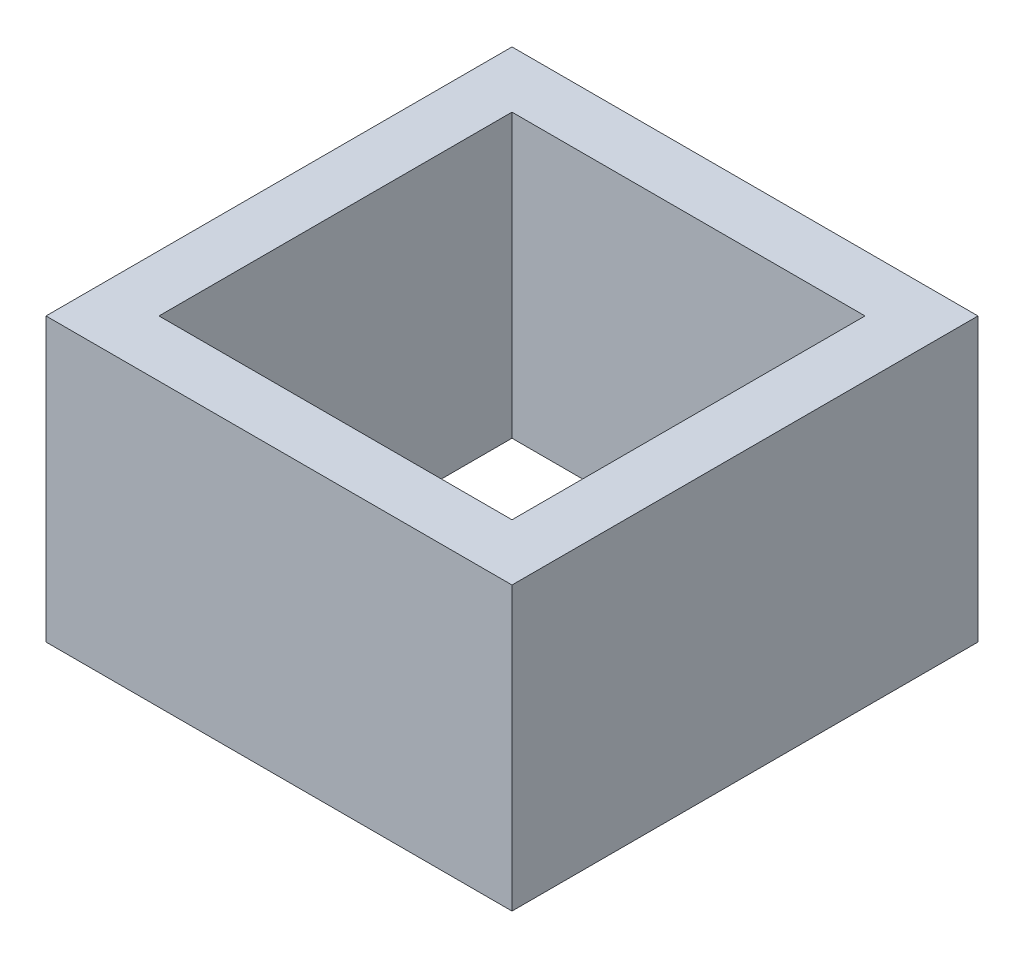
SolidWorks part; units mm, degrees
material "2014-O"
ref_plane "Plan de face" through (0, 0, 0) normal (0, 0, 1) x (1, 0, 0)
ref_plane "Plan de dessus" through (0, 0, 0) normal (0, 1, 0) x (1, 0, 0)
ref_plane "Plan de droite" through (0, 0, 0) normal (1, 0, 0) x (0, 0, -1)
sketch "Esquisse1" plane through (0, 0, 0) normal (0, 1, 0) x (1, 0, 0)
  line L1 (-125, -125) -> (125, -125)
  line L2 (-125, -125) -> (-125, 125)
  line L3 (-125, 125) -> (125, 125)
  line L4 (125, -125) -> (125, 125)
  line L5 (-125, -125) -> (125, 125) construction
  line L6 (-125, 125) -> (125, -125) construction
  line L7 (-165, -165) -> (165, -165)
  line L8 (-165, -165) -> (-165, 165)
  line L9 (-165, 165) -> (165, 165)
  line L10 (165, -165) -> (165, 165)
  line L11 (-165, -165) -> (165, 165) construction
  line L12 (-165, 165) -> (165, -165) construction
  point P0 (0, 0)
  point P6 (0, 0)
  dimension "D1" = 250
  dimension "D2" = 250
  dimension "D3" = 40
  dimension "D4" = 40
extrude "Boss.-Extru.1" add sketch "Esquisse1" against normal blind 200
